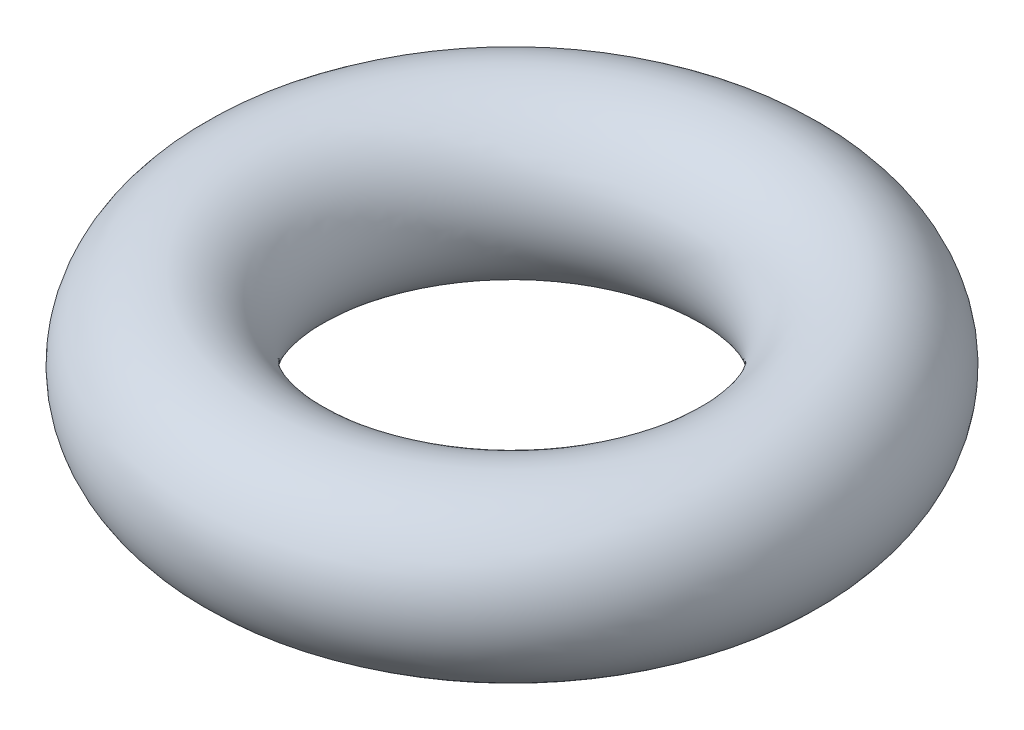
SolidWorks part; units mm, degrees
material "POLYURETHANE (11671)"
ref_plane "Front Plane" through (0, 0, 0) normal (0, 0, 1) x (1, 0, 0)
ref_plane "Top Plane" through (0, 0, 0) normal (0, 1, 0) x (1, 0, 0)
ref_plane "Right Plane" through (0, 0, 0) normal (1, 0, 0) x (0, 0, -1)
sketch "Sketch1" plane through (0, 0, 0) normal (0, 0, 1) x (1, 0, 0)
  line L0 (0, 18.9642) -> (0, -10.6951) construction
  circle A0 centre (7.5, 0) radius 2.5
  dimension "D1" = 5
  dimension "D2" = 7.5
  dimension "D3" = 7.5
revolve "Revolve1" add sketch "Sketch1" angle 360 about L0
